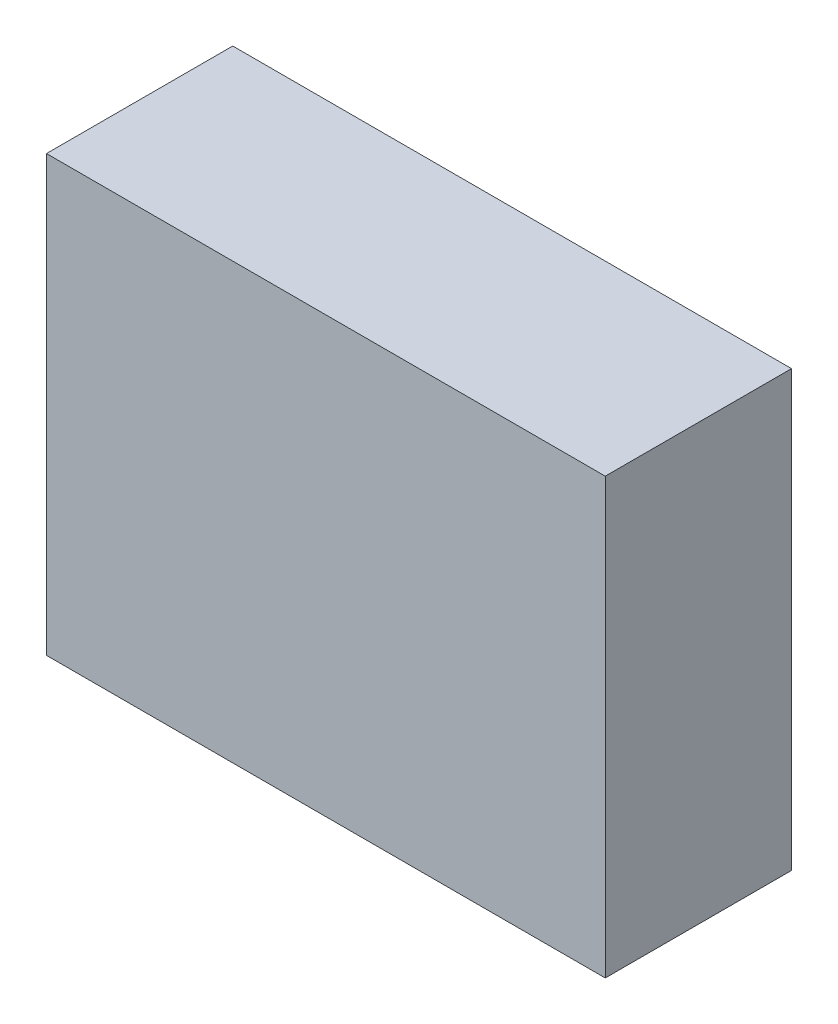
SolidWorks part; units mm, degrees
material "Polyethylene Cross-Linked"
ref_plane "Front Plane" through (0, 0, 0) normal (0, 0, 1) x (1, 0, 0)
ref_plane "Top Plane" through (0, 0, 0) normal (0, 1, 0) x (1, 0, 0)
ref_plane "Right Plane" through (0, 0, 0) normal (1, 0, 0) x (0, 0, -1)
sketch "Sketch1" plane through (0, 0, 0) normal (0, 0, 1) x (1, 0, 0)
  line L1 (0, 0) -> (900, 0)
  line L2 (0, 0) -> (0, 700)
  line L3 (0, 700) -> (900, 700)
  line L4 (900, 0) -> (900, 700)
  dimension "Length" = 900
  dimension "Width" = 700
extrude "Boss-Extrude1" add sketch "Sketch1" along normal blind 300
shell "Shell1" thickness 10
